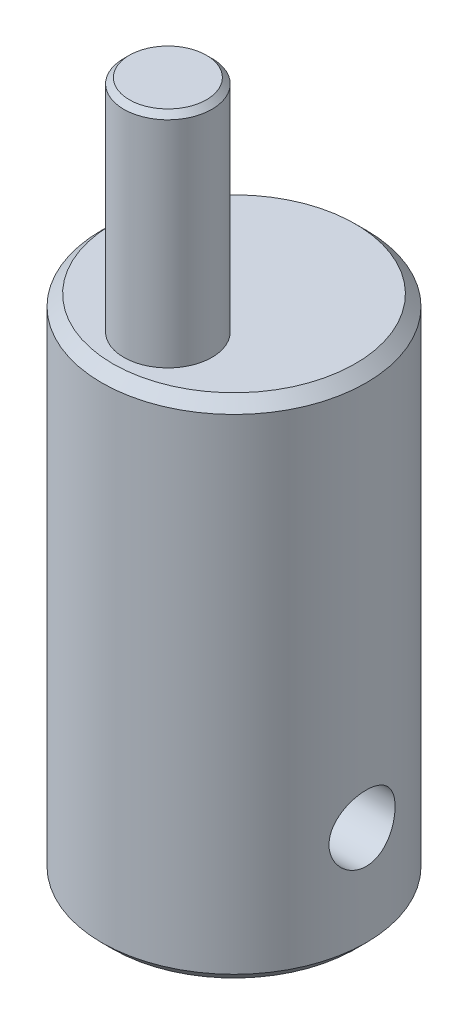
SolidWorks part; units mm, degrees
ref_plane "Front Plane" through (0, 0, 0) normal (0, 0, 1) x (1, 0, 0)
ref_plane "Top Plane" through (0, 0, 0) normal (0, 1, 0) x (1, 0, 0)
ref_plane "Right Plane" through (0, 0, 0) normal (1, 0, 0) x (0, 0, -1)
sketch "Sketch1" plane through (0, 0, 0) normal (0, 1, 0) x (1, 0, 0)
  circle A0 centre (0, 0) radius 6
  dimension "D1" = 12
extrude "Boss-Extrude1" add sketch "Sketch1" along normal blind 23
sketch "Sketch2" plane through (0, 23, 0) normal (0, 1, 0) x (1, 0, 0)
  circle A0 centre (0, -3) radius 2
  point P2 (0, 0)
  dimension "D2" = 4
  dimension "D1" = 3
extrude "Boss-Extrude2" add sketch "Sketch2" along normal blind 10
sketch "Sketch3" plane through (0, 0, 0) normal (1, 0, 0) x (0, 0, -1)
  circle A0 centre (0, 5) radius 1.5
  point P2 (0, 0)
  dimension "D1" = 3
  dimension "D2" = 5
extrude "Cut-Extrude1" cut sketch "Sketch3" against normal through all both and the other way through all
chamfer "Chamfer1" distance 0.25 angle 45 1 edges at (0, 33, 5)
chamfer "Chamfer2" distance 0.5 angle 45 2 edges at (0, 0, 6) (0, 23, 6)
